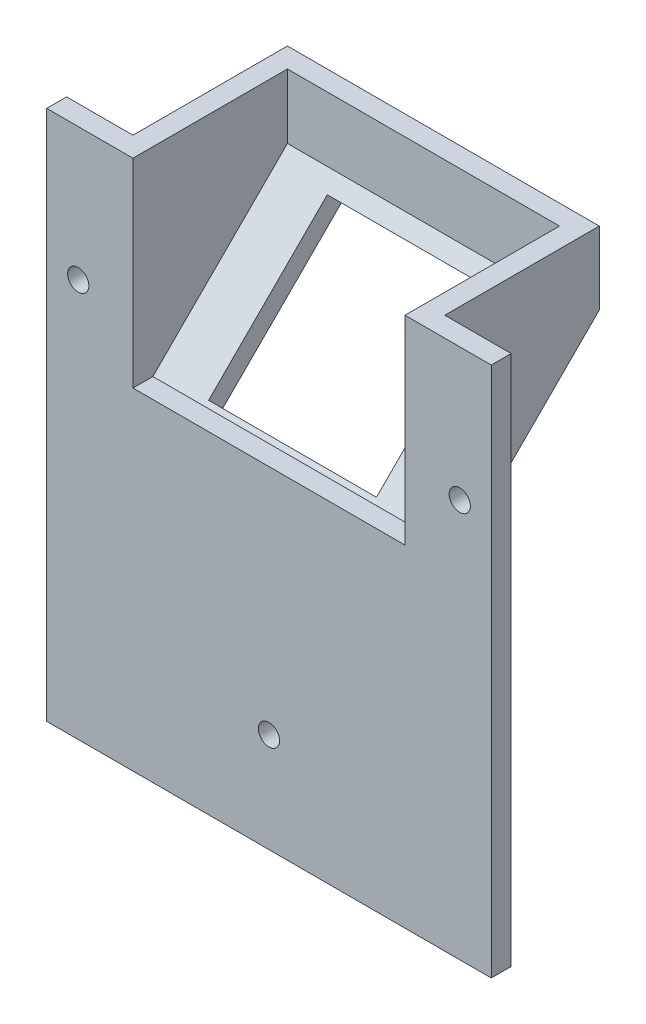
SolidWorks part; units mm, degrees
material "ABS PC"
ref_plane "Ön Düzlem" through (0, 0, 0) normal (0, 0, 1) x (1, 0, 0)
ref_plane "Üst Düzlem" through (0, 0, 0) normal (0, 1, 0) x (1, 0, 0)
ref_plane "Sağ Düzlem" through (0, 0, 0) normal (1, 0, 0) x (0, 0, -1)
sketch "Çizim1" plane through (0, 0, 0) normal (0, 0, 1) x (1, 0, 0)
  line L1 (67, 0) -> (0, 0)
  line L2 (67, 0) -> (67, 80)
  line L3 (67, 80) -> (57, 80)
  line L4 (0, 0) -> (0, 80)
  line L7 (10, 80) -> (10, 50)
  line L8 (10, 50) -> (57, 50)
  line L9 (57, 50) -> (57, 80)
  line L10 (10, 80) -> (0, 80)
  dimension "D1" = 10
  dimension "D2" = 80
  dimension "D3" = 47
  dimension "D4" = 30
  dimension "D5" = 10
extrude "Yükseklik-Ekstrüzyon1" add sketch "Çizim1" along normal blind 3
sketch "Çizim2" plane through (10, 0, 0) normal (1, 0, 0) x (0, 0, -1)
  line L0 (-3, 80) -> (23.2806, 80)
  line L1 (23.2806, 80) -> (23.2806, 69.0379)
  line L2 (23.2806, 69.0379) -> (0, 45.7574)
  line L3 (0, 45.7574) -> (-3, 45.7574)
  line L4 (-3, 0) -> (-3, 80) construction
  line L5 (-3, 45.7574) -> (-3, 80)
  line L6 (0, 0) -> (0, 80) construction
  line L7 (0, 50) -> (20.2806, 70.2806) construction
  line L8 (20.2806, 70.2806) -> (20.2806, 80) construction
  line L9 (14.8564, 60.6137) -> (12.735, 62.735) construction
  line L10 (0, 50) -> (2.1213, 47.8787) construction
  dimension "D1" = 45
  dimension "D2" = 3
  dimension "D3" = 3
  dimension "D4" = 3
extrude "Yükseklik-Ekstrüzyon2" add sketch "Çizim2" along normal blind 3 separate body
sketch "Çizim4" plane through (57, 0, 0) normal (-1, 0, 0) x (0, 0, 1)
  line L0 (3, 80) -> (-23.2806, 80)
  line L1 (-23.2806, 80) -> (-23.2806, 69.0379)
  line L2 (-23.2806, 69.0379) -> (0, 45.7574)
  line L3 (0, 45.7574) -> (3, 45.7574)
  line L4 (3, 80) -> (3, 0) construction
  line L5 (3, 45.7574) -> (3, 80)
extrude "Yükseklik-Ekstrüzyon3" add sketch "Çizim4" along normal blind 3
sketch "Çizim5" plane through (54, 0, 0) normal (-1, 0, 0) x (0, 0, 1)
  line L0 (0, 45.7574) -> (-23.2806, 69.0379)
  line L1 (-23.2806, 69.0379) -> (-23.2806, 80)
  line L2 (-23.2806, 80) -> (-20.2806, 80)
  line L3 (3, 80) -> (-23.2806, 80) construction
  line L4 (-20.2806, 80) -> (-20.2806, 70.2806)
  line L5 (-20.2806, 70.2806) -> (0, 50)
  line L6 (0, 50) -> (0, 45.7574)
  line L7 (0, 50) -> (-2.1213, 47.8787) construction
  line L8 (-20.8746, 66.632) -> (-18.7533, 68.7533) construction
  dimension "D1" = 3
  dimension "D2" = 3
extrude "Yükseklik-Ekstrüzyon4" add sketch "Çizim5" along normal up to surface (41 mm away) up to face at (13, 64.1105, -8.1122)
sketch "Çizim6" plane through (0, 0, 3) normal (0, 0, 1) x (1, 0, 0)
  line L0 (33.5, 0) -> (33.5, 15) construction
  line L2 (0, 0) -> (67, 0) construction
  line L12 (13, 80) -> (0, 80) construction
  line L13 (0, 80) -> (0, 0) construction
  line L14 (67, 0) -> (67, 80) construction
  line L15 (67, 80) -> (54, 80) construction
  point P1 (33.5, 15)
  point P5 (4.75, 60)
  point P12 (62.25, 60)
  point P21 (4.75, 60)
  point P25 (33.5, 15)
  point P29 (62.25, 60)
  dimension "D1" = 15
  dimension "D2" = 20
  dimension "D3" = 4.75
  dimension "D4" = 4.75
  dimension "D5" = 20
hole_wizard "M3 Boşluklu Delik1" positions "Çizim6" profile "Çizim7" hole size "M3" standard "ISO"
sketch "Çizim7" plane through (62.25, 60, 3) normal (1, 0, 0) x (0, -1, 0)
  line L0 (0, 0) -> (0, 10.9614)
  line L1 (0, 10.9614) -> (1.6, 10)
  line L2 (1.6, 10) -> (1.6, 0)
  line L5 (1.6, 0) -> (0, 0)
  line L10 (0, 10.9614) -> (-1.6, 10) construction
  line L11 (0, -6.35) -> (0, 107.95) construction
  dimension "Hole Dia." = 3.2
  dimension "Hole Depth" = 10
  dimension "Drill Angle" = 118
sketch "Çizim10" plane through (0, 22.8787, 22.8787) normal (0, -0.7071, -0.7071) x (1, 0, 0)
  line L0 (33.5, -65.279) -> (33.5, -48.779) construction
  line L1 (57, -65.279) -> (10, -65.279) construction
  line L3 (46.15, -36.129) -> (20.85, -36.129)
  line L4 (46.15, -36.129) -> (46.15, -61.429)
  line L5 (46.15, -61.429) -> (20.85, -61.429)
  line L6 (20.85, -36.129) -> (20.85, -61.429)
  line L7 (46.15, -36.129) -> (20.85, -61.429) construction
  line L8 (46.15, -61.429) -> (20.85, -36.129) construction
  dimension "D1" = 16.5
  dimension "D2" = 25.3
  dimension "D3" = 25.3
extrude "Kes-Ekstrüzyon1" cut sketch "Çizim10" against normal blind 10
